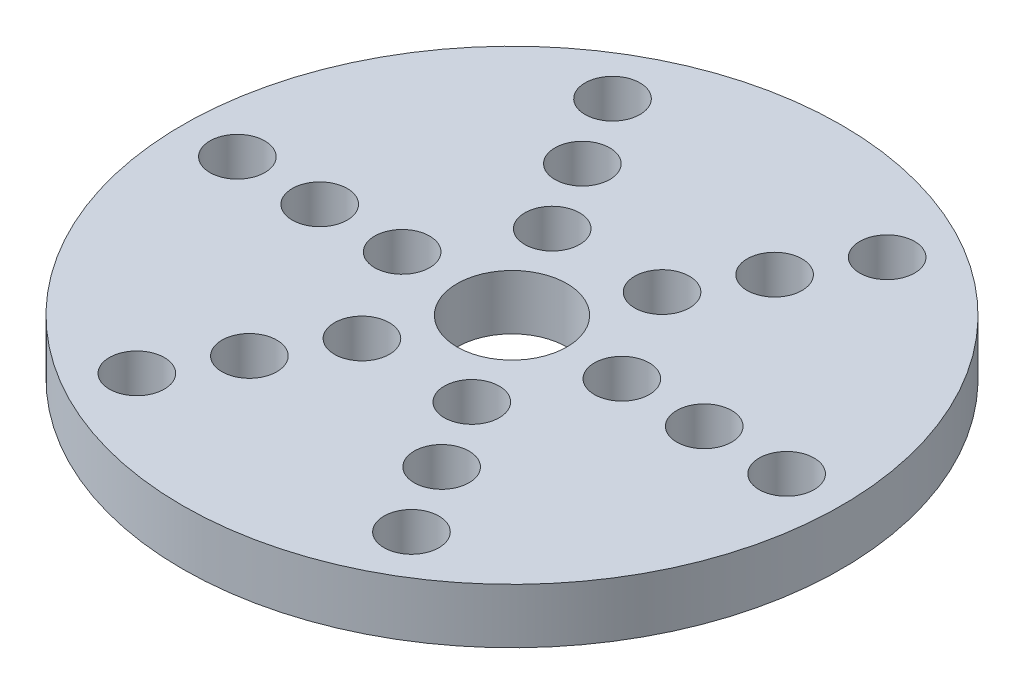
SolidWorks part; units mm, degrees
ref_plane "Front Plane" through (0, 0, 0) normal (0, 0, 1) x (1, 0, 0)
ref_plane "Top Plane" through (0, 0, 0) normal (0, 1, 0) x (1, 0, 0)
ref_plane "Right Plane" through (0, 0, 0) normal (1, 0, 0) x (0, 0, -1)
sketch "Sketch1" plane through (0, 0, 0) normal (0, 1, 0) x (1, 0, 0)
  line L0 (0, 105.5872) -> (0, -105.5872) construction
  line L1 (-168.8657, 0) -> (168.8657, 0) construction
  line L2 (0, 0) -> (-30, 51.9615) construction
  arc A0 (0, 60) -> (-60, 0) centre (0, 0) ccw
  circle A5 centre (-25, 43.3013) radius 5
  circle A6 centre (-17.5, 30.3109) radius 5
  circle A7 centre (-10, 17.3205) radius 5
  arc A8 (0, 10) -> (-10, 0) centre (0, 0) ccw
  circle A9 centre (25, 43.3013) radius 5
  circle A10 centre (17.5, 30.3109) radius 5
  circle A11 centre (10, 17.3205) radius 5
  circle A12 centre (50, 0) radius 5
  circle A13 centre (35, 0) radius 5
  circle A14 centre (20, 0) radius 5
  circle A15 centre (25, -43.3013) radius 5
  circle A16 centre (17.5, -30.3109) radius 5
  circle A17 centre (10, -17.3205) radius 5
  circle A18 centre (-25, -43.3013) radius 5
  circle A19 centre (-17.5, -30.3109) radius 5
  circle A20 centre (-10, -17.3205) radius 5
  circle A21 centre (-50, 0) radius 5
  circle A22 centre (-35, 0) radius 5
  circle A23 centre (-20, 0) radius 5
  arc A24 (60, 0) -> (0, 60) centre (0, 0) ccw
  arc A25 (10, 0) -> (0, 10) centre (0, 0) ccw
  arc A26 (0, -60) -> (60, 0) centre (0, 0) ccw
  arc A27 (0, -10) -> (10, 0) centre (0, 0) ccw
  arc A28 (-60, 0) -> (0, -60) centre (0, 0) ccw
  arc A29 (-10, 0) -> (0, -10) centre (0, 0) ccw
  point P6 (0, 0)
  point P9 (0, 0)
  point P51 (0, 0)
  point P65 (0, 0)
  dimension "D1" = 120
  dimension "D2" = 60
  dimension "D3" = 10
  dimension "D7" = 20
  dimension "D8" = 6
  dimension "D9" = 4
  dimension "D4" = 50
  dimension "D5" = 35
  dimension "D6" = 20
extrude "Boss-Extrude2" add sketch "Sketch1" along normal blind 10
